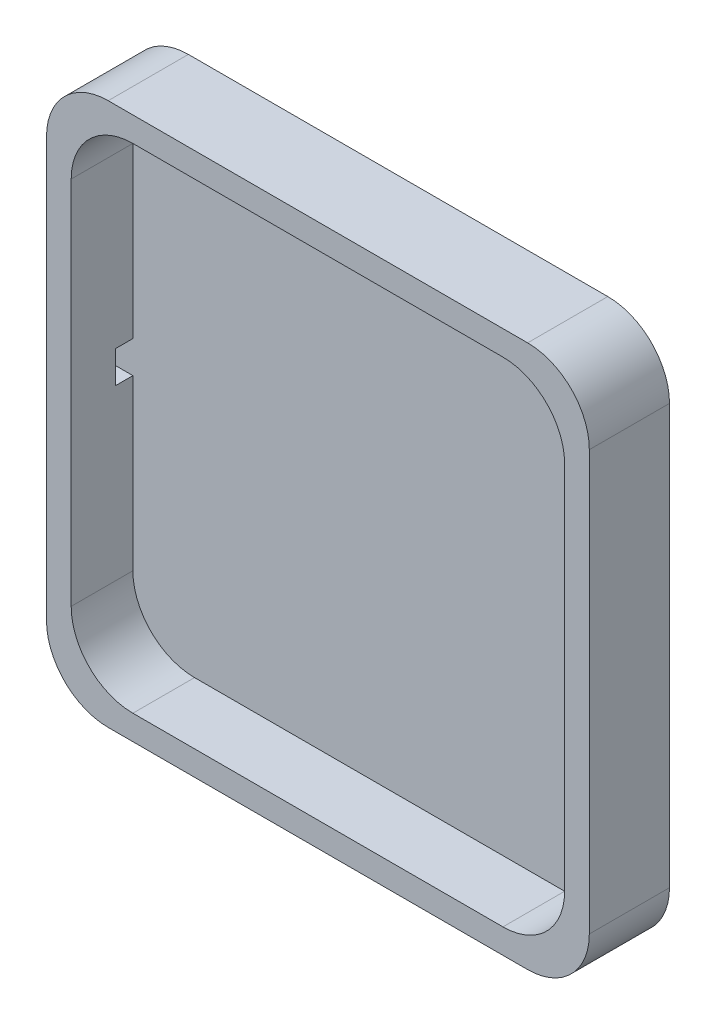
SolidWorks part; units mm, degrees
ref_plane "前视基准面" through (0, 0, 0) normal (0, 0, 1) x (1, 0, 0)
ref_plane "上视基准面" through (0, 0, 0) normal (0, 1, 0) x (1, 0, 0)
ref_plane "右视基准面" through (0, 0, 0) normal (1, 0, 0) x (0, 0, -1)
other "Configuration Table"
sketch "草图1" plane through (0, 0, 0) normal (0, 0, 1) x (1, 0, 0)
  line L0 (-17, 22) -> (17, 22)
  line L1 (-22, 17) -> (-22, -17)
  line L2 (-17, -22) -> (17, -22)
  line L3 (22, 17) -> (22, -17)
  arc A0 (-17, 22) -> (-22, 17) centre (-17, 17) ccw
  arc A1 (22, 17) -> (17, 22) centre (17, 17) ccw
  arc A2 (-17, -22) -> (-22, -17) centre (-17, -17) cw
  arc A3 (22, -17) -> (17, -22) centre (17, -17) cw
  dimension "D1" = 5
  dimension "D2" = 5
  dimension "D3" = 5
  dimension "D4" = 5
extrude "凸台-拉伸1" add sketch "草图1" along normal blind 1.5
sketch "草图2" plane through (0, 0, 1.5) normal (0, 0, 1) x (1, 0, 0)
  line L0 (-17, 22) -> (17, 22)
  line L1 (-22, 17) -> (-22, -17)
  line L2 (-17, -22) -> (17, -22)
  line L3 (22, 17) -> (22, -17)
  line L5 (-15, 20) -> (15, 20)
  line L7 (20, 15) -> (20, -15)
  line L9 (15, -20) -> (-15, -20)
  line L11 (-20, -15) -> (-20, 15)
  arc A0 (-17, 22) -> (-22, 17) centre (-17, 17) ccw
  arc A1 (22, 17) -> (17, 22) centre (17, 17) ccw
  arc A2 (-17, -22) -> (-22, -17) centre (-17, -17) cw
  arc A3 (22, -17) -> (17, -22) centre (17, -17) cw
  arc A4 (20, 15) -> (15, 20) centre (15, 15) ccw
  arc A5 (15, -20) -> (20, -15) centre (15, -15) ccw
  arc A6 (-20, -15) -> (-15, -20) centre (-15, -15) ccw
  arc A7 (-20, 15) -> (-15, 20) centre (-15, 15) cw
  dimension "D1" = 5
  dimension "D2" = 5
  dimension "D3" = 5
  dimension "D4" = 5
  dimension "D5" = 5
extrude "凸台-拉伸2" add sketch "草图2" along normal blind 5
sketch "草图4" [suppressed] plane through (0, 0, 6.5) normal (0, 0, 1) x (1, 0, 0)
  line L0 (-17, 22) -> (17, 22)
  line L1 (-22, 17) -> (-22, -17)
  line L2 (-17, -22) -> (17, -22)
  line L3 (22, 17) -> (22, -17)
  line L5 (-14, 9) -> (-14, -9)
  line L7 (-9, -14) -> (9, -14)
  line L9 (14, -9) -> (14, 9)
  line L11 (9, 14) -> (-9, 14)
  arc A0 (-17, 22) -> (-22, 17) centre (-17, 17) ccw
  arc A1 (22, 17) -> (17, 22) centre (17, 17) ccw
  arc A2 (-17, -22) -> (-22, -17) centre (-17, -17) cw
  arc A3 (22, -17) -> (17, -22) centre (17, -17) cw
  arc A4 (9, 14) -> (14, 9) centre (9, 9) cw
  arc A5 (14, -9) -> (9, -14) centre (9, -9) cw
  arc A6 (-9, -14) -> (-14, -9) centre (-9, -9) cw
  arc A7 (-14, 9) -> (-9, 14) centre (-9, 9) cw
  dimension "D1" = 5
sketch "草图5" plane through (-20, 0, 0) normal (1, 0, 0) x (0, 0, -1)
  line L0 (-1.5, 1.3) -> (-1.5, -1.3)
  line L2 (-1.5, 1.3) -> (-2.9, 1.3)
  line L3 (-2.9, 1.3) -> (-2.9, -1.3)
  line L4 (-2.9, -1.3) -> (-1.5, -1.3)
extrude "切除-拉伸1" cut sketch "草图5" against normal through all
